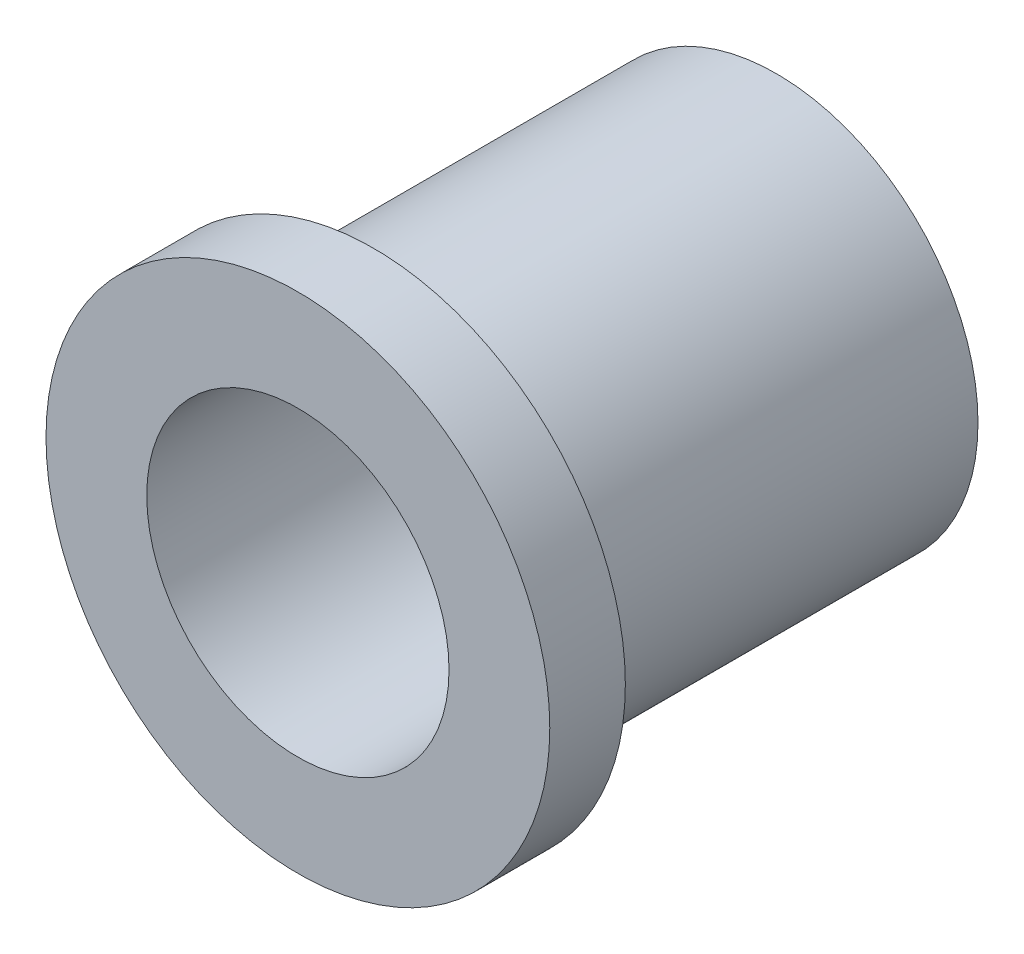
SolidWorks part; units mm, degrees
ref_plane "Front Plane" through (0, 0, 0) normal (0, 0, 1) x (1, 0, 0)
ref_plane "Top Plane" through (0, 0, 0) normal (0, 1, 0) x (1, 0, 0)
ref_plane "Right Plane" through (0, 0, 0) normal (1, 0, 0) x (0, 0, -1)
sketch "Sketch1" plane through (0, 0, 0) normal (0, 0, 1) x (1, 0, 0)
  circle A0 centre (0, 0) radius 9.525
  circle A1 centre (0, 0) radius 12.7
  dimension "D1" = 25.4
  dimension "D2" = 19.05
extrude "Boss-Extrude1" add sketch "Sketch1" along normal mid plane 25.4
sketch "Sketch2" plane through (0, 0, 12.7) normal (0, 0, 1) x (1, 0, 0)
  circle A0 centre (0, 0) radius 9.525
  circle A1 centre (0, 0) radius 15.875
  dimension "D1" = 31.75
  dimension "D2" = 19.05
extrude "Boss-Extrude2" add sketch "Sketch2" along normal blind 4.7625
